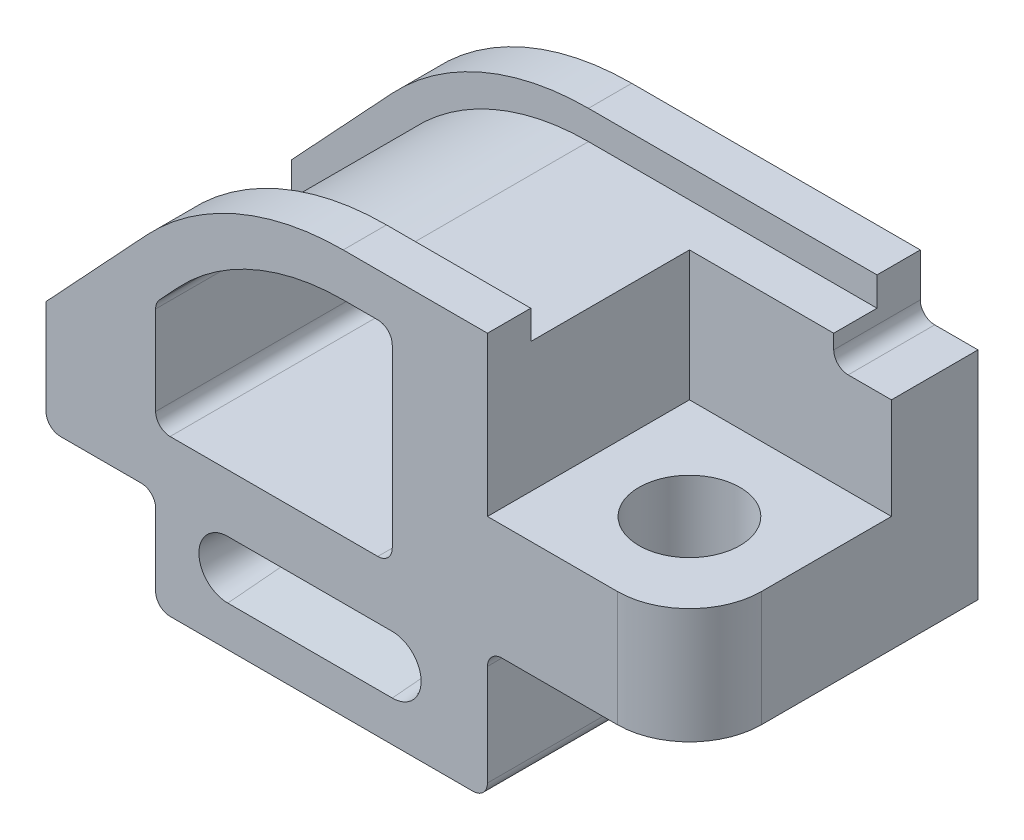
SolidWorks part; units mm, degrees
material "Copper"
ref_plane "Front Plane" through (0, 0, 0) normal (0, 0, 1) x (1, 0, 0)
ref_plane "Top Plane" through (0, 0, 0) normal (0, 1, 0) x (1, 0, 0)
ref_plane "Right Plane" through (0, 0, 0) normal (1, 0, 0) x (0, 0, -1)
sketch "Sketch1" plane through (0, 0, 0) normal (0, 0, 1) x (1, 0, 0)
  line L0 (0, 0) -> (38, 0)
  line L1 (38, 0) -> (38, -35)
  line L2 (38, -35) -> (153, -35)
  line L3 (153, -35) -> (153, 10)
  line L4 (153, 10) -> (223, 10)
  line L5 (223, 10) -> (223, 85)
  line L6 (223, 85) -> (203, 85)
  line L7 (203, 85) -> (203, 105)
  line L8 (203, 105) -> (103, 105)
  line L9 (34.8429, 75.3645) -> (0, 38)
  line L10 (0, 38) -> (0, 0)
  arc A0 (103, 105) -> (34.8429, 75.3645) centre (103, 11.807) ccw
  dimension "D1" = 35
  dimension "D2" = 115
  dimension "D3" = 70
  dimension "D4" = 45
  dimension "D5" = 75
  dimension "D6" = 140
  dimension "D7" = 20
  dimension "D8" = 100
  dimension "D9" = 223
  dimension "D10" = 38
  dimension "D11" = 43
extrude "Boss-Extrude1" add sketch "Sketch1" along normal mid plane 100
sketch "Sketch2" plane through (0, 0, 50) normal (0, 0, 1) x (1, 0, 0)
  line L0 (120, 90) -> (120, 19)
  line L1 (120, 19) -> (38, 19)
  line L2 (38, 0) -> (38, -35) construction
  line L3 (45.8132, 65.1345) -> (10.9703, 27.77)
  line L4 (45.8132, 65.1345) -> (38, 56.7558)
  line L5 (38, 56.7558) -> (38, 19)
  line L6 (203, 90) -> (103, 90)
  line L7 (120, 90) -> (103, 90)
  arc A2 (103, 90) -> (45.8132, 65.1345) centre (103, 11.807) ccw
  arc A3 (103, 90) -> (45.8132, 65.1345) centre (103, 11.807) ccw
  dimension "D3" = 19
  dimension "D4" = 33
  dimension "D1" = 15
  dimension "D2" = 15
extrude "Cut-Extrude1" cut sketch "Sketch2" against normal offset from surface (85 mm away) 15 up to face at (114.0634, 37.5377, -50)
sketch "Sketch3" plane through (0, 0, 0) normal (0, 0, 1) x (1, 0, 0)
  line L2 (203, 85) -> (203, 105) construction
  line L3 (203, 105) -> (103, 105) construction
  line L4 (203, 95) -> (103, 95)
  line L5 (42.1565, 68.5445) -> (7.3135, 31.18)
  line L6 (203, 95) -> (103, 95)
  line L7 (42.1565, 68.5445) -> (0, 23.3372)
  line L8 (34.8429, 75.3645) -> (0, 38) construction
  line L9 (0, 38) -> (0, 0) construction
  line L10 (203, 95) -> (203, 105)
  line L11 (203, 105) -> (103, 105)
  line L12 (34.8429, 75.3645) -> (0, 38)
  line L13 (0, 38) -> (0, 23.3372)
  arc A1 (103, 105) -> (34.8429, 75.3645) centre (103, 11.807) ccw construction
  arc A2 (103, 95) -> (42.1565, 68.5445) centre (103, 11.807) ccw
  arc A3 (103, 95) -> (42.1565, 68.5445) centre (103, 11.807) ccw
  arc A4 (103, 105) -> (34.8429, 75.3645) centre (103, 11.807) ccw
  dimension "D1" = 10
extrude "Cut-Extrude2" cut sketch "Sketch3" against normal mid plane 70
sketch "Sketch4" plane through (0, 105, 0) normal (0, 1, 0) x (1, 0, 0)
  line L1 (223, -50) -> (153, -50)
  line L2 (223, -50) -> (223, 20)
  line L3 (223, 20) -> (153, 20)
  line L4 (153, -50) -> (153, 20)
  dimension "D1" = 70
extrude "Cut-Extrude3" cut sketch "Sketch4" against normal blind 55
sketch "Sketch5" plane through (0, 50, 0) normal (0, 1, 0) x (1, 0, 0)
  line L0 (223, 20) -> (153, -50) construction
  circle A0 centre (188, -15) radius 17.5
  dimension "D1" = 35
extrude "Cut-Extrude4" cut sketch "Sketch5" against normal through all and the other way through all
fillet "Fillet1" radius 25 1 edges at (223, 30, 50)
fillet "Fillet2" radius 5 6 edges at (203, 85, -35) (153, -35, 0) (153, 10, 0) (38, -35, 0) (38, 0, 0) (0, 0, 0)
fillet "Fillet3" radius 5 4 edges at (38, 56.7558, 7.5) (38, 19, 7.5) (120, 19, 7.5) (120, 90, 7.5)
sketch "Sketch6" plane through (0, 0, 50) normal (0, 0, 1) x (1, 0, 0)
  line L0 (63, -11) -> (120, -11) construction
  line L1 (63, -1) -> (120, -1)
  line L2 (63, -21) -> (120, -21)
  line L3 (115, 19) -> (43, 19) construction
  line L4 (38, -5) -> (38, -30) construction
  arc A0 (63, -1) -> (63, -21) centre (63, -11) ccw
  arc A1 (120, -21) -> (120, -1) centre (120, -11) ccw
  point P2 (91.5, -11)
  dimension "D3" = 10
  dimension "D1" = 20
  dimension "D2" = 25
  dimension "D4" = 57
extrude "Cut-Extrude5" cut sketch "Sketch6" against normal blind 25 draft 5
mirror "Mirror1" about plane through (0, 0, 0) normal (0, 0, 1) of "Cut-Extrude5"
equation "\"A\" = 223"
equation "\"B\" = 38"
equation "\"C\"= 35"
equation "\"D\" = 43"
equation "\"D9@Sketch1\"=\"A\""
equation "\"D10@Sketch1\"=\"B\""
equation "\"D1@Sketch5\"=\"C\""
equation "\"D11@Sketch1\"=\"D\""
